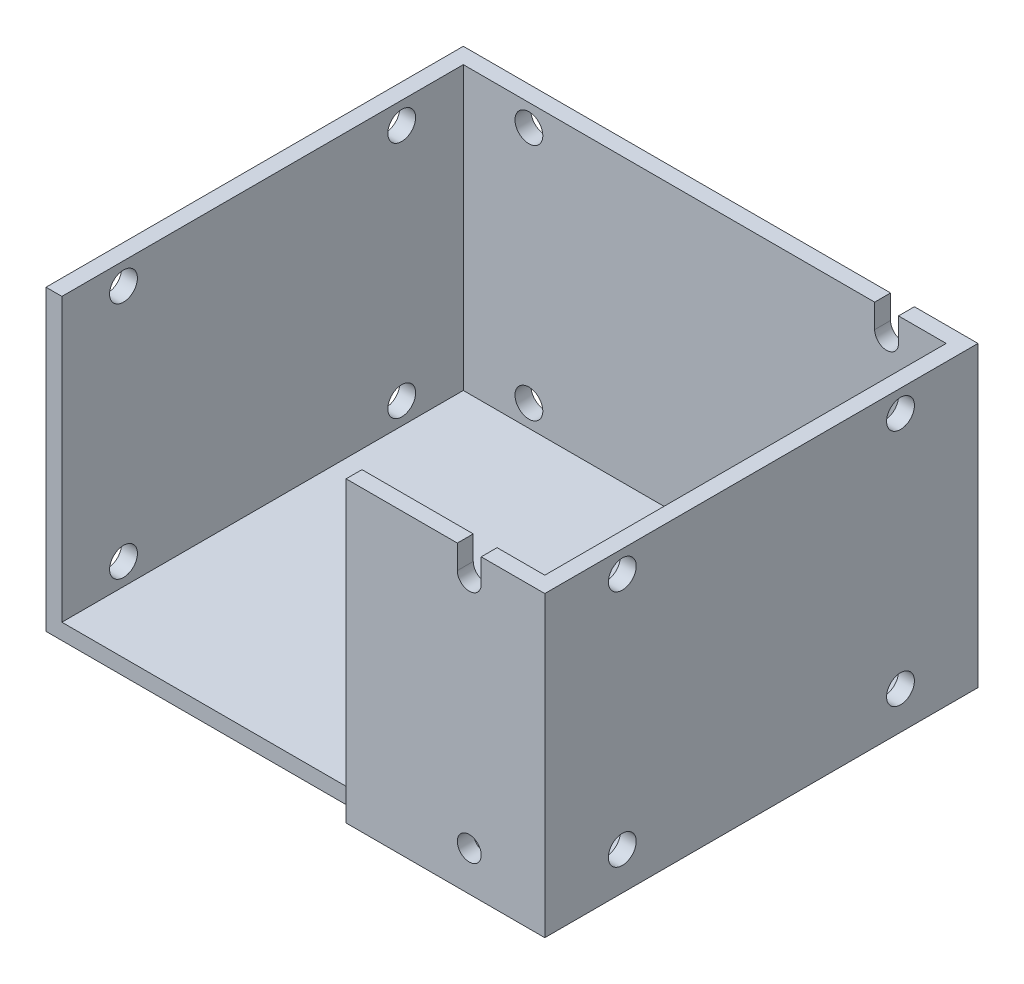
SolidWorks part; units mm, degrees
ref_plane "Alzado" through (0, 0, 0) normal (0, 0, 1) x (1, 0, 0)
ref_plane "Planta" through (0, 0, 0) normal (0, 1, 0) x (1, 0, 0)
ref_plane "Vista lateral" through (0, 0, 0) normal (1, 0, 0) x (0, 0, -1)
sketch "Croquis1" plane through (0, 0, 0) normal (0, 1, 0) x (1, 0, 0)
  line L1 (-60.75, 50.5) -> (60.75, 50.5)
  line L2 (-60.75, 50.5) -> (-60.75, -50.5)
  line L3 (-60.75, -50.5) -> (60.75, -50.5)
  line L4 (60.75, 50.5) -> (60.75, -50.5)
  line L5 (-60.75, 50.5) -> (60.75, -50.5) construction
  line L6 (-60.75, -50.5) -> (60.75, 50.5) construction
  line L7 (0, 54.5) -> (60.75, 54.5)
  line L8 (0, 54.5) -> (-60.75, 54.5)
  line L10 (-64.75, 0) -> (-64.75, 54.5)
  line L11 (-64.75, 54.5) -> (-60.75, 54.5)
  line L13 (64.75, 0) -> (64.75, 54.5)
  line L14 (64.75, 54.5) -> (60.75, 54.5)
  line L15 (64.75, 0) -> (64.75, -50.5)
  line L16 (64.75, -50.5) -> (60.75, -50.5)
  line L17 (-64.75, 0) -> (-64.75, -50.5)
  line L18 (-64.75, -50.5) -> (-60.75, -50.5)
  point P0 (0, 0)
  dimension "D1" = 101
  dimension "D2" = 121.5
extrude "Saliente-Extruir2" add sketch "Croquis1" along normal blind 4 contours L2 L1 L4 L3
sketch "Croquis2" plane through (0, 0, 0) normal (0, 1, 0) x (1, 0, 0)
  line L2 (60.75, -50.5) -> (64.75, -50.5)
  line L3 (-60.75, -50.5) -> (-64.75, -50.5)
  line L4 (-64.75, -50.5) -> (-64.75, 54.5)
  line L5 (-64.75, 54.5) -> (60.75, 54.5)
  line L6 (64.75, 54.5) -> (64.75, -50.5)
  line L7 (64.75, 54.5) -> (60.75, 54.5)
  line L10 (-60.75, -50.5) -> (60.75, -50.5)
  line L11 (60.75, -50.5) -> (60.75, 50.5)
  line L12 (60.75, 50.5) -> (-60.75, 50.5)
  line L13 (-60.75, 50.5) -> (-60.75, -50.5)
  line L15 (60.75, -50.5) -> (60.75, 50.5)
  line L16 (60.75, 50.5) -> (-60.75, 50.5)
  line L17 (-60.75, 50.5) -> (-60.75, -50.5)
  dimension "D1" = 0
  dimension "D2" = 4
  dimension "D3" = 4
extrude "Saliente-Extruir3" add sketch "Croquis2" along normal blind 75
sketch "Croquis3" plane through (0, 0, 0) normal (0, 1, 0) x (1, 0, 0)
  line L0 (64.75, -50.5) -> (64.75, -54.5)
  line L1 (64.75, -54.5) -> (14.75, -54.5)
  line L2 (14.75, -54.5) -> (14.75, -50.5)
  line L3 (-60.75, -50.5) -> (60.75, -50.5) construction
  line L4 (14.75, -50.5) -> (64.75, -50.5)
  dimension "D1" = 4
  dimension "D2" = 50
extrude "Saliente-Extruir4" add sketch "Croquis3" along normal blind 75
sketch "Croquis4" plane through (64.75, 0, 0) normal (1, 0, 0) x (0, 0, -1)
  line L0 (50.5, 75) -> (50.5, 0) construction
  line L3 (-50.5, 75) -> (-50.5, 0) construction
  line L4 (-54.5, 75) -> (54.5, 75) construction
  line L5 (-54.5, 0) -> (54.5, 0) construction
  line L6 (54.5, 75) -> (54.5, 0) construction
  line L7 (-54.5, 75) -> (-54.5, 0) construction
  line L8 (-54.5, 4) -> (54.5, 4) construction
  line L9 (-50.5, 37.5) -> (50.5, 37.5) construction
  line L10 (0, 75) -> (0, 73)
  line L11 (-35, 73) -> (35, 73)
  line L12 (0, 4) -> (0, 6)
  line L13 (-35, 6) -> (35, 6)
  circle A0 centre (35, 69.5) radius 3.5
  circle A1 centre (-35, 69.5) radius 3.5
  circle A2 centre (35, 9.5) radius 3.5
  circle A3 centre (-35, 9.5) radius 3.5
  point P23 (0, 73)
  point P30 (35, 37.5)
  point P32 (0, 6)
  dimension "D6" = 7
  dimension "D7" = 7
  dimension "D9" = 7
  dimension "D10" = 7
  dimension "D11" = 60
  dimension "D1" = 4
  dimension "D2" = 4
  dimension "D3" = 4
  dimension "D4" = 2
  dimension "D5" = 70
  dimension "D8" = 2
extrude "Cortar-Extruir1" cut sketch "Croquis4" against normal up to surface (129.5 mm away) contours A1 | A2 | A3 | A0 up to face at (-64.75, 37.5, -2)
sketch "Croquis5" plane through (0, 0, -54.5) normal (0, 0, -1) x (-1, 0, 0)
  line L0 (-64.75, 4) -> (64.75, 4) construction
  line L1 (44.25, 75) -> (44.25, 73)
  line L2 (-64.75, 75) -> (-64.75, 0) construction
  line L3 (64.75, 75) -> (64.75, 0) construction
  line L4 (-64.75, 0) -> (64.75, 0) construction
  line L5 (-60.75, 75) -> (-60.75, 0) construction
  line L6 (-64.75, 75) -> (64.75, 75) construction
  line L7 (60.75, 75) -> (60.75, 0) construction
  line L8 (-60.75, 37.5) -> (60.75, 37.5) construction
  line L9 (47.75, 69.5) -> (60.75, 69.5)
  line L10 (44.25, 4) -> (44.25, 6)
  line L11 (47.75, 9.5) -> (60.75, 9.5)
  circle A0 centre (44.25, 69.5) radius 3.5
  circle A1 centre (44.25, 9.5) radius 3.5
  point P22 (0, 6)
  point P23 (47.75, 37.5)
  point P28 (-47.75, 37.5)
  dimension "D6" = 13
  dimension "D5" = 7
  dimension "D8" = 7
  dimension "D1" = 4
  dimension "D2" = 4
  dimension "D3" = 4
  dimension "D4" = 2
  dimension "D7" = 2
  dimension "D9" = 13
extrude "Cortar-Extruir2" cut sketch "Croquis5" against normal up to surface (4 mm away) contours A0 | A1 up to face at (0, 39.5, -50.5)
sketch "Croquis6" plane through (0, 0, 0) normal (0, 0, 1) x (1, 0, 0)
  line L0 (60.75, 75) -> (60.75, 0) construction
  line L1 (64.75, 75) -> (-64.75, 75) construction
  line L2 (64.75, 0) -> (-64.75, 0) construction
  line L3 (64.75, 75) -> (64.75, 0) construction
  line L4 (64.75, 4) -> (-64.75, 4) construction
  line L5 (-64.75, 75) -> (-64.75, 0) construction
  line L6 (-60.75, 75) -> (-60.75, 0) construction
  line L7 (60.75, 69) -> (48.75, 69)
  line L8 (60.75, 10) -> (48.75, 10)
  line L9 (48.75, 69) -> (48.75, 75)
  line L10 (48.75, 75) -> (45.75, 75)
  line L11 (42.75, 69) -> (42.75, 75)
  line L12 (42.75, 75) -> (45.75, 75)
  line L13 (45.75, 13) -> (45.75, 4)
  arc A0 (42.75, 69) -> (48.75, 69) centre (45.75, 69) ccw
  circle A1 centre (45.75, 10) radius 3
  dimension "D5" = 6
  dimension "D7" = 6
  dimension "D1" = 4
  dimension "D2" = 4
  dimension "D3" = 4
  dimension "D4" = 12
  dimension "D6" = 12
  dimension "D8" = 9
extrude "Cortar-Extruir3" cut sketch "Croquis6" along normal up to surface (109 mm away) from surface at -54.5 contours L11 A0 L9 L10 L12 | L13 A1 | A1 L13 up to face at (39.75, 37.5, 54.5) starting at face at (-47.75, 69.5, -54.5)
